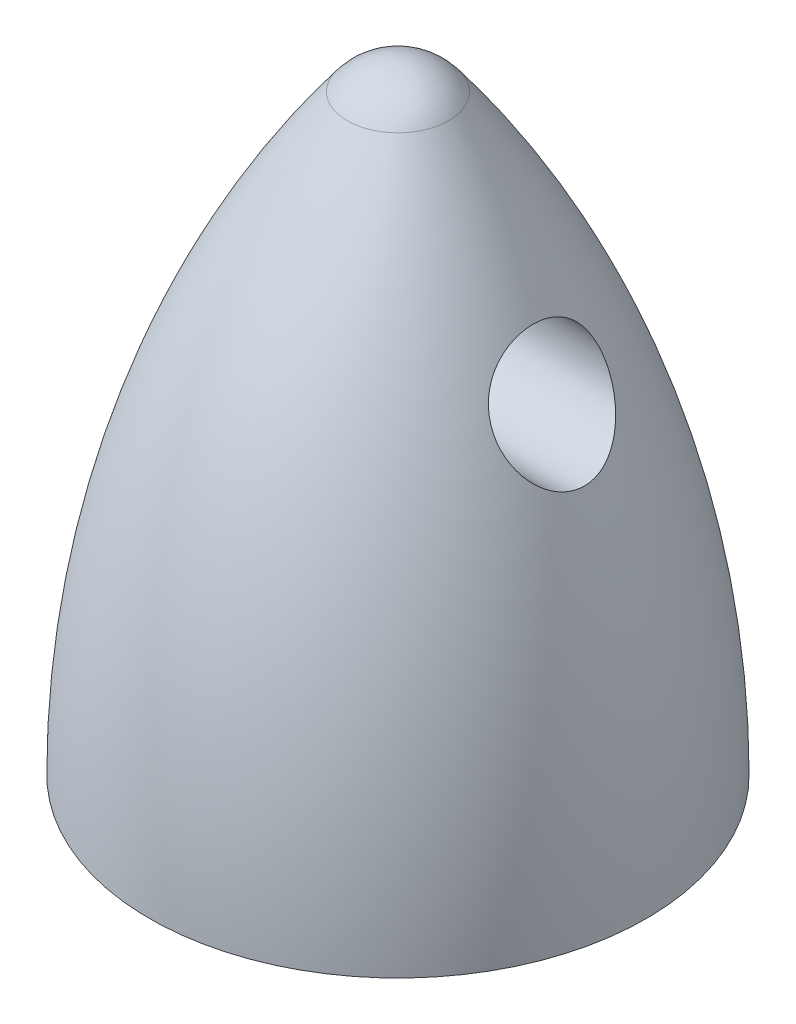
SolidWorks part; units mm, degrees
ref_plane "Front Plane" through (0, 0, 0) normal (0, 0, 1) x (1, 0, 0)
ref_plane "Top Plane" through (0, 0, 0) normal (0, 1, 0) x (1, 0, 0)
ref_plane "Right Plane" through (0, 0, 0) normal (1, 0, 0) x (0, 0, -1)
sketch "Sketch1" plane through (0, 0, 0) normal (1, 0, 0) x (0, 0, -1)
  line L0 (0, 0) -> (0, 67.3418) construction
  line L1 (0, 0) -> (6.5, 0)
  line L2 (0, 16.1709) -> (0, 0)
  arc A0 (6.5, 0) -> (1.325, 15.5022) centre (-19.3065, 0) ccw
  arc A1 (1.325, 15.5022) -> (0, 16.1709) centre (-0.014, 14.4961) ccw
  dimension "D1" = 13
revolve "Revolve1" add sketch "Sketch1" angle 360 about L0
sketch "Sketch2" plane through (0, 0, 0) normal (0, -1, 0) x (1, 0, 0)
  circle A0 centre (0, 0) radius 5.2829
extrude "Cut-Extrude1" cut sketch "Sketch2" against normal blind 3.8
sketch "Sketch3" plane through (0, 0, 0) normal (1, 0, 0) x (0, 0, -1)
  line L0 (0, 0) -> (0, 16.1709) construction
  line L1 (-6.5, 0) -> (6.5, 0) construction
  circle A0 centre (0, 10.5) radius 1.5
  dimension "D2" = 3
  dimension "D1" = 10.5
extrude "Cut-Extrude2" cut sketch "Sketch3" against normal through all and the other way through all
